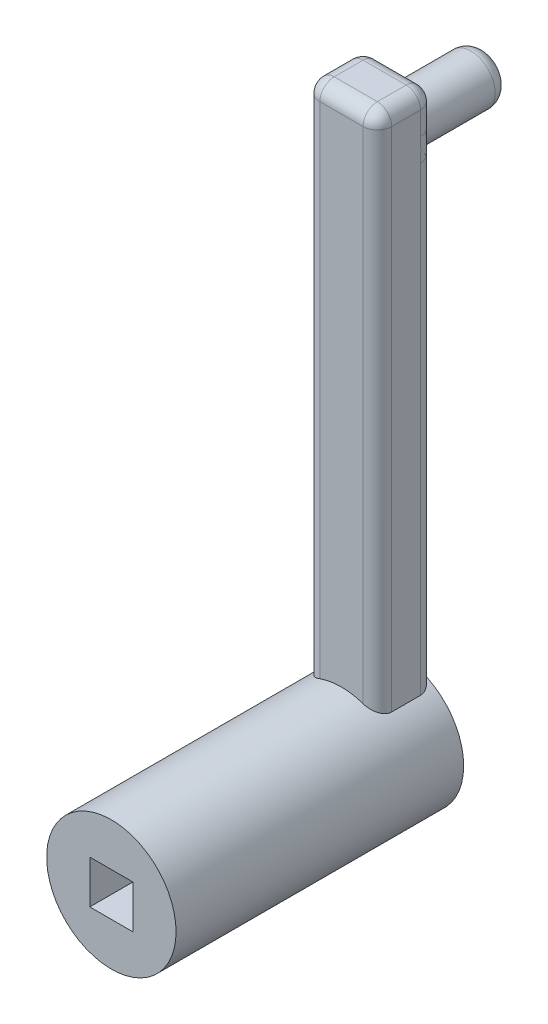
SolidWorks part; units mm, degrees
material "ABS"
ref_plane "Front Plane" through (0, 0, 0) normal (0, 0, 1) x (1, 0, 0)
ref_plane "Top Plane" through (0, 0, 0) normal (0, 1, 0) x (1, 0, 0)
ref_plane "Right Plane" through (0, 0, 0) normal (1, 0, 0) x (0, 0, -1)
sketch "Sketch1" plane through (0, 0, 0) normal (0, 0, 1) x (1, 0, 0)
  circle A0 centre (0, 0) radius 5.715
  dimension "D1" = 11.43
extrude "Boss-Extrude1" add sketch "Sketch1" against normal blind 25.4
sketch "Sketch2" plane through (0, 0, 0) normal (1, 0, 0) x (0, 0, -1)
  line L0 (25.4, 0) -> (25.4, 50.8)
  line L1 (25.4, -5.715) -> (25.4, 5.715) construction
  line L2 (25.4, 50.8) -> (20.32, 50.8)
  line L3 (20.32, 50.8) -> (20.32, 0)
  line L4 (6.985, 0) -> (-6.985, 0) construction
  line L5 (20.32, 0) -> (25.4, 0)
  dimension "D1" = 50.8
  dimension "D2" = 5.08
extrude "Boss-Extrude2" add sketch "Sketch2" along normal mid plane 6.35
sketch "Sketch3" plane through (0, 0, -25.4) normal (0, 0, -1) x (-1, 0, 0)
  line L0 (-3.175, 50.8) -> (3.175, 50.8) construction
  line L1 (0, 18.161) -> (0, -18.161) construction
  circle A0 centre (0, 46.482) radius 2.159
  dimension "D1" = 4.318
  dimension "D2" = 4.318
extrude "Boss-Extrude3" add sketch "Sketch3" along normal blind 7.62
fillet "Fillet1" radius 1.27 9 edges at (-3.175, 50.8, -22.86) (0, 50.8, -25.4) (3.175, 50.8, -22.86) (0, 50.8, -20.32) (-3.175, 27.776, -20.32) (3.175, 27.776, -20.32) (-3.175, 27.776, -25.4) (3.175, 27.776, -25.4) (-2.159, 46.482, -33.02)
sketch "Sketch4" plane through (0, 0, 0) normal (0, 0, 1) x (1, 0, 0)
  line L1 (-1.905, -1.905) -> (1.905, -1.905)
  line L2 (-1.905, -1.905) -> (-1.905, 1.905)
  line L3 (-1.905, 1.905) -> (1.905, 1.905)
  line L4 (1.905, -1.905) -> (1.905, 1.905)
  line L5 (-1.905, -1.905) -> (1.905, 1.905) construction
  line L6 (-1.905, 1.905) -> (1.905, -1.905) construction
  point P0 (0, 0)
  dimension "D1" = 3.81
extrude "Cut-Extrude1" cut sketch "Sketch4" against normal blind 7.62
